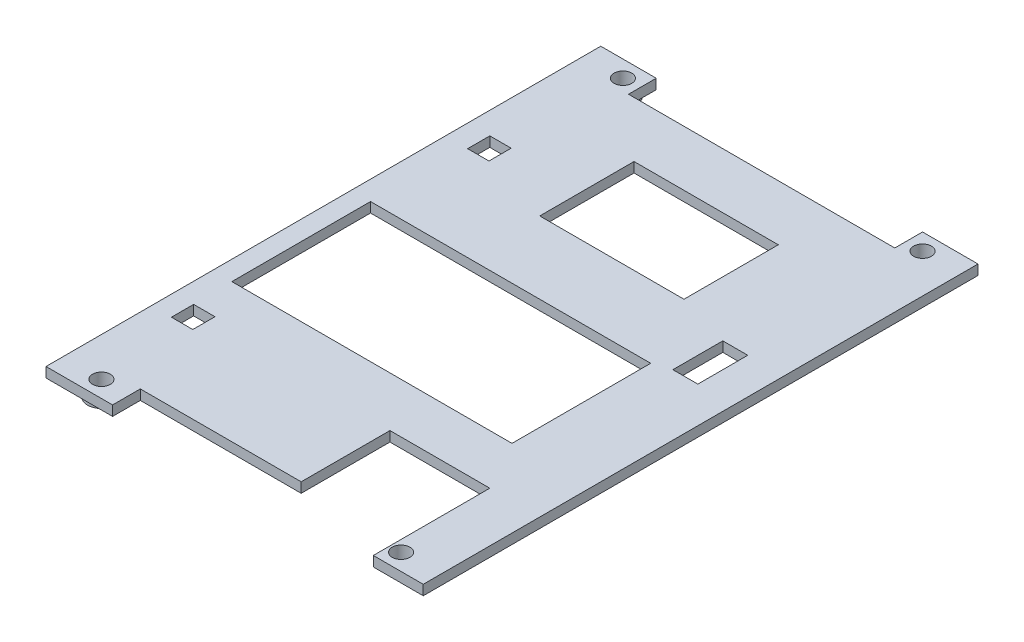
SolidWorks part; units mm, degrees
ref_plane "前视基准面" through (0, 0, 0) normal (0, 0, 1) x (1, 0, 0)
ref_plane "上视基准面" through (0, 0, 0) normal (0, 1, 0) x (1, 0, 0)
ref_plane "右视基准面" through (0, 0, 0) normal (1, 0, 0) x (0, 0, -1)
sketch "草图1" plane through (0, 0, 0) normal (0, 1, 0) x (1, 0, 0)
  line L1 (0, 0) -> (68, 0)
  line L2 (0, 0) -> (0, -100)
  line L3 (0, -100) -> (68, -100)
  line L4 (68, 0) -> (68, -100)
  dimension "D1" = 68
  dimension "D2" = 100
extrude "凸台-拉伸1" add sketch "草图1" along normal blind 1.8
sketch "草图2" plane through (0, 1.8, 0) normal (0, 1, 0) x (1, 0, 0)
  line L0 (68, 0) -> (0, 0) construction
  line L1 (10, 0) -> (58, 0)
  line L2 (10, 0) -> (10, -5)
  line L3 (10, -5) -> (58, -5)
  line L4 (58, 0) -> (58, -5)
  line L5 (0, 0) -> (0, -100) construction
  line L6 (21, -15) -> (47, -15)
  line L7 (21, -15) -> (21, -32)
  line L8 (21, -32) -> (47, -32)
  line L9 (47, -15) -> (47, -32)
  line L10 (68, -100) -> (68, 0) construction
  line L12 (4, -24) -> (7.8464, -24)
  line L13 (4, -24) -> (4, -28)
  line L14 (4, -28) -> (7.8464, -28)
  line L15 (7.8464, -24) -> (7.8464, -28)
  line L16 (3.6119, -77) -> (7.4582, -77)
  line L17 (3.5, -45) -> (54, -45)
  line L18 (3.5, -45) -> (3.5, -70)
  line L19 (3.5, -70) -> (54, -70)
  line L20 (54, -45) -> (54, -70)
  line L21 (3.6119, -77) -> (3.6119, -81)
  line L22 (3.6119, -81) -> (7.4582, -81)
  line L23 (7.4582, -77) -> (7.4582, -81)
  line L24 (0, -100) -> (68, -100) construction
  line L26 (12, -100) -> (36, -100)
  line L27 (12, -100) -> (12, -95)
  line L28 (12, -95) -> (36, -95)
  line L29 (36, -100) -> (36, -95)
  line L30 (41, -100) -> (59, -100)
  line L31 (41, -100) -> (41, -83.2083)
  line L32 (41, -83.2083) -> (59, -83.2083)
  line L33 (59, -100) -> (59, -83.2083)
  line L34 (57, -35) -> (61.5, -35)
  line L35 (57, -35) -> (57, -44)
  line L36 (57, -44) -> (61.5, -44)
  line L37 (61.5, -35) -> (61.5, -44)
  dimension "D1" = 5
  dimension "D2" = 10
  dimension "D3" = 10
  dimension "D4" = 15
  dimension "D5" = 21
  dimension "D6" = 21
  dimension "D7" = 32
  dimension "D8" = 24
  dimension "D9" = 4
  dimension "D10" = 4
  dimension "D11" = 25
  dimension "D12" = 3.5
  dimension "D13" = 14
  dimension "D14" = 19
  dimension "D15" = 45
  dimension "D16" = 30
  dimension "D17" = 12
  dimension "D18" = 36
  dimension "D19" = 5
  dimension "D20" = 9
  dimension "D21" = 27
  dimension "D22" = 6.5
  dimension "D23" = 11
  dimension "D24" = 35
  dimension "D25" = 9
extrude "切除-拉伸1" cut sketch "草图2" against normal blind 1.8
sketch "草图4" plane through (0, 0, 0) normal (0, -1, 0) x (1, 0, 0)
  circle A0 centre (7, 97) radius 1.4
  circle A1 centre (7, 97) radius 2.5
  circle A2 centre (61, 97) radius 1.4
  circle A3 centre (61, 97) radius 2
  circle A4 centre (61, 3) radius 1.4
  circle A5 centre (61, 3) radius 2.5
  circle A6 centre (7, 3) radius 1.4
  circle A7 centre (7, 3) radius 2.5
extrude "凸台-拉伸3" add sketch "草图4" along normal blind 1
sketch "草图6" plane through (0, 0, 0) normal (0, -1, 0) x (1, 0, 0)
  circle A0 centre (7, 97) radius 1.4
  circle A1 centre (61, 97) radius 1.4
  circle A2 centre (61, 3) radius 1.4
  circle A3 centre (7, 3) radius 1.4
extrude "切除-拉伸3" cut sketch "草图6" against normal blind 14
sketch "草图8" plane through (0, 1.8, 0) normal (0, 1, 0) x (1, 0, 0)
  line L1 (36, -95) -> (41, -95)
  line L2 (36, -95) -> (36, -100)
  line L3 (36, -100) -> (41, -100)
  line L4 (41, -95) -> (41, -100)
  line L5 (36, -100) -> (36, -95) construction
  line L6 (59, -100) -> (68, -100) construction
  line L7 (41, -83.2083) -> (59, -83.2083)
  line L8 (41, -83.2083) -> (41, -79)
  line L9 (41, -79) -> (59, -79)
  line L10 (59, -83.2083) -> (59, -79)
  line L11 (59, -100) -> (59, -83.2083) construction
  line L12 (41, -83.2083) -> (41, -100) construction
  point P4 (41, -100)
  point P16 (58.9996, -83.2083)
  dimension "D2" = 21
extrude "切除-拉伸4" cut sketch "草图8" against normal blind 10
sketch "草图9" plane through (0, 1.8, 0) normal (0, 1, 0) x (1, 0, 0)
  circle A0 centre (7, -3) radius 1.6
  circle A1 centre (61, -3) radius 1.6
  circle A2 centre (61, -97) radius 1.6
  circle A3 centre (7, -97) radius 1.6
extrude "切除-拉伸5" cut sketch "草图9" against normal blind 10
